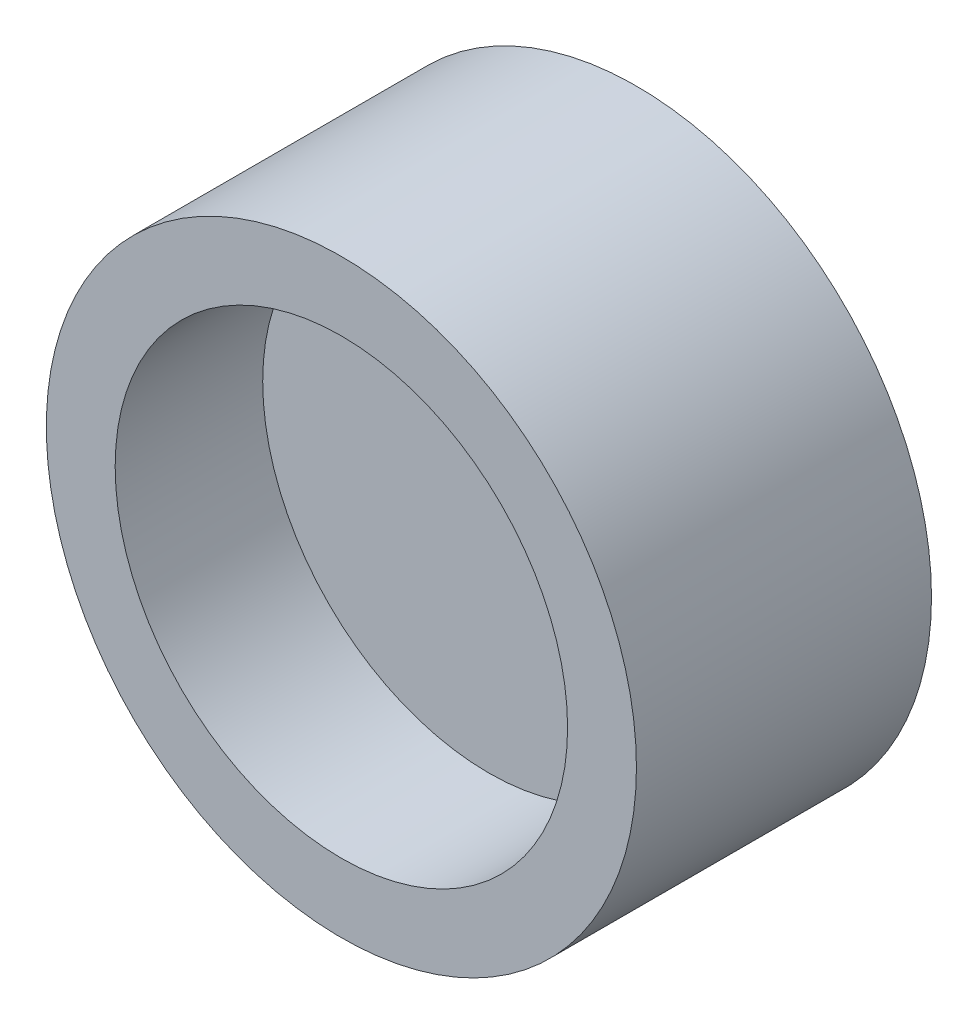
SolidWorks part; units mm, degrees
ref_plane "Front" through (0, 0, 0) normal (0, 0, 1) x (1, 0, 0)
ref_plane "Top" through (0, 0, 0) normal (0, 1, 0) x (1, 0, 0)
ref_plane "Right" through (0, 0, 0) normal (1, 0, 0) x (0, 0, -1)
sketch "Эскиз1" plane through (0, 0, 0) normal (0, 0, 1) x (1, 0, 0)
  circle A0 centre (0, 0) radius 3
extrude "Бобышка-Вытянуть1" add sketch "Эскиз1" along normal blind 3
sketch "Эскиз2" plane through (0, 0, 3) normal (0, 0, 1) x (1, 0, 0)
  circle A0 centre (0, 0) radius 2.3
extrude "Вырез-Вытянуть1" cut sketch "Эскиз2" against normal blind 1.5
